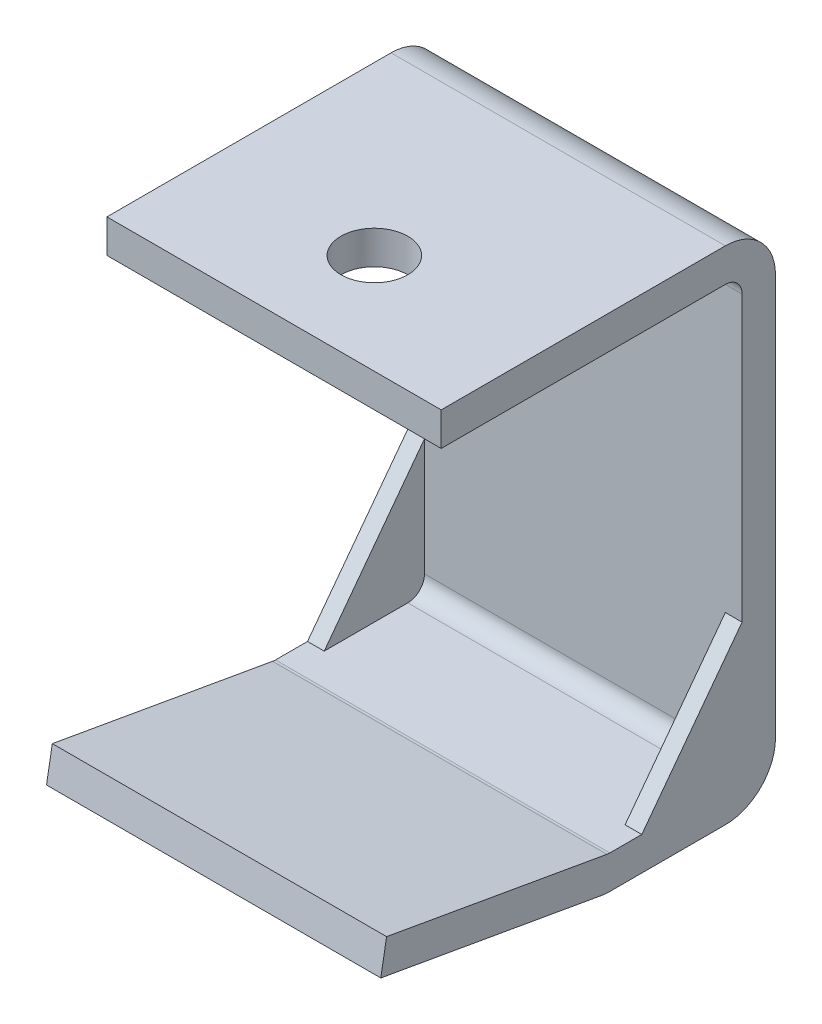
SolidWorks part; units mm, degrees
ref_plane "front" through (0, 0, 0) normal (0, 0, 1) x (1, 0, 0)
ref_plane "top" through (0, 0, 0) normal (0, 1, 0) x (1, 0, 0)
ref_plane "right" through (0, 0, 0) normal (1, 0, 0) x (0, 0, -1)
sketch "Sketch1" plane through (0, 0, 0) normal (1, 0, 0) x (0, 0, -1)
  line L0 (0, 0) -> (0, 82.55)
  line L1 (0, 82.55) -> (-57.15, 82.55)
  line L4 (-67.5238, 7.4276) -> (-25.4, 0)
  line L5 (-25.4, 0) -> (0, 0)
  dimension "D1" = 82.55
  dimension "D2" = 57.15
  dimension "D3" = 10
  dimension "D4" = 42.7736
  dimension "D5" = 25.4
extrude "Base-Extrude-Thin" add sketch "Sketch1" along normal mid plane 63.5 thin
sketch "Sketch2" plane through (0, 88.9, 0) normal (0, 1, 0) x (-1, 0, 0)
  line L0 (0, 50) -> (0, -50) construction
  line L1 (-31.75, 57.15) -> (31.75, 57.15) construction
  circle A0 centre (0, 38.1) radius 6.35
  dimension "D1" = 12.7
  dimension "D2" = 19.05
extrude "Cut-Extrude1" cut sketch "Sketch2" against normal up to next
sketch "Sketch3" plane through (31.75, 0, 0) normal (1, 0, 0) x (0, 0, -1)
  line L0 (-25.1222, 0) -> (-3.175, 0) construction
  line L1 (0, 3.175) -> (0, 79.375) construction
  line L2 (-19.05, 0) -> (-3.175, 0)
  line L3 (0, 3.175) -> (0, 25.4)
  line L4 (-19.05, 0) -> (0, 25.4)
  arc A0 (-3.175, 0) -> (0, 3.175) centre (-3.175, 3.175) ccw construction
  arc A1 (-3.175, 0) -> (0, 3.175) centre (-3.175, 3.175) ccw
  dimension "D1" = 25.4
  dimension "D2" = 19.05
extrude "Boss-Extrude1" add sketch "Sketch3" against normal blind 3.175
mirror "Mirror1" about plane through (0, 0, 0) normal (1, 0, 0) of "Boss-Extrude1"
